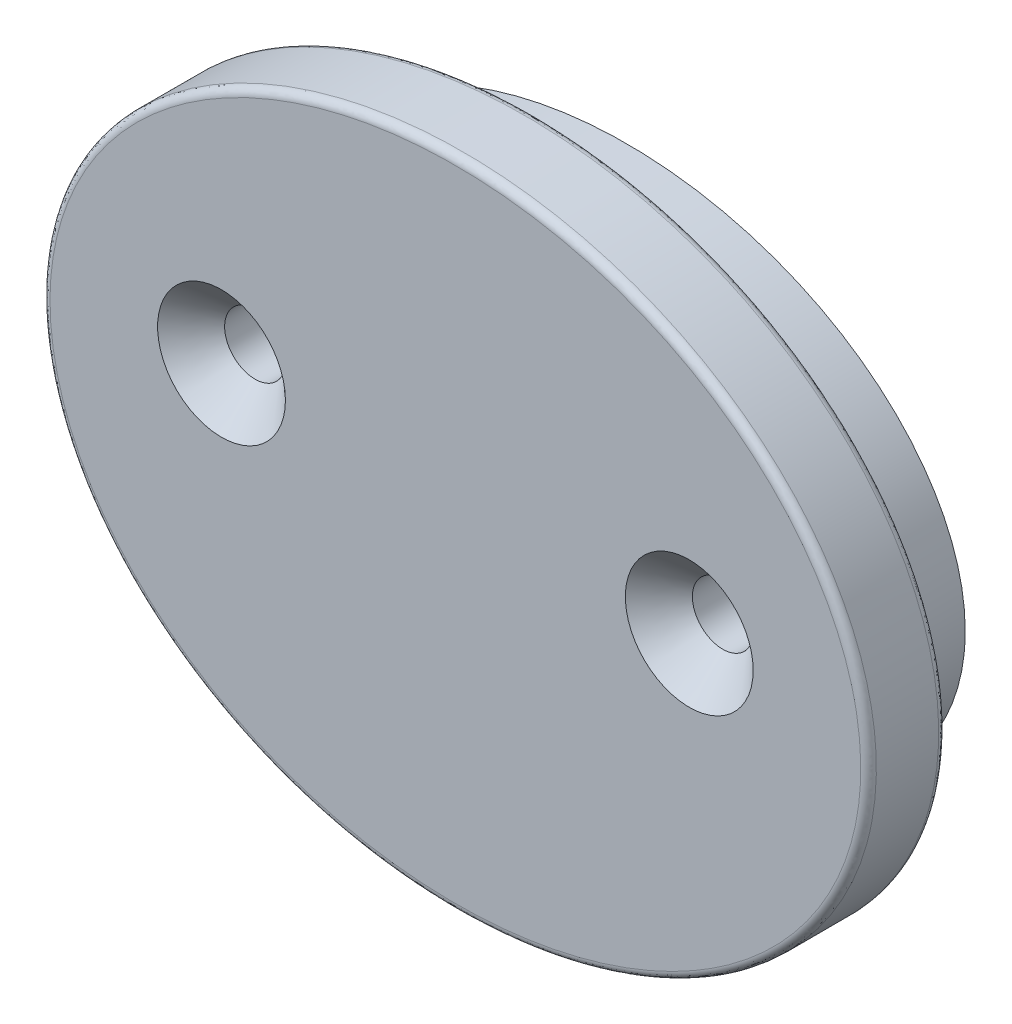
SolidWorks part; units mm, degrees
ref_plane "Ebene vorne" through (0, 0, 0) normal (0, 0, 1) x (1, 0, 0)
ref_plane "Ebene oben" through (0, 0, 0) normal (0, 1, 0) x (1, 0, 0)
ref_plane "Ebene rechts" through (0, 0, 0) normal (1, 0, 0) x (0, 0, -1)
sketch "Skizze1" plane through (0, 0, 0) normal (0, 0, 1) x (1, 0, 0)
  ellipse E0 centre (0, 0) end of major axis (21.7, 0) minor radius 16.2
extrude "Aufsatz-Linear austragen1" add sketch "Skizze1" along normal blind 6
sketch "Skizze2" plane through (0, 0, 6) normal (0, 0, 1) x (1, 0, 0)
  ellipse E0 centre (0, 0) end of major axis (26.5, 0) minor radius 21
extrude "Aufsatz-Linear austragen2" add sketch "Skizze2" along normal blind 5
sketch "Skizze3" plane through (0, 0, 11) normal (0, 0, 1) x (1, 0, 0)
  point P0 (-15, 2)
  point P1 (15, 2)
  dimension "D1" = 2
  dimension "D2" = 2
  dimension "D3" = 15
  dimension "D4" = 15
hole_wizard "Formsenkung für M3.5 Linsensenkschraube1" positions "3D-Skizze1" profile "Skizze4" countersink size "M3.5" standard "ANSI Metrisch" end condition through all
sketch3d "3D-Skizze1"
  point P0 (-15, 2, 11)
  point P3 (15, 2, 11)
sketch "Skizze4" plane through (-15, 2, 11) normal (1, 0, 0) x (0, -1, 0)
  line L0 (0, 0) -> (0, 11)
  line L1 (0, 11) -> (1.95, 11)
  line L2 (1.95, 11) -> (1.95, 2.15)
  line L3 (1.95, 2.15) -> (4.1, 0)
  line L5 (4.1, 0) -> (0, 0)
  line L6 (-1.95, 2.15) -> (-4.1, 0) construction
  line L11 (0, -6.35) -> (0, 107.95) construction
  dimension "Bohrerdurchmesser" = 3.9
  dimension "Bohrungstiefe" = 11
  dimension "Senkdurchmesser (Oben)" = 8.2
  dimension "Senkwinkel (Oben)" = 90
sketch "Skizze5" plane through (0, 0, 11) normal (0, 0, 1) x (1, 0, 0)
  point P0 (0, 0)
sketch "Skizze7" plane through (0, 0, 6) normal (0, 0, -1) x (-1, 0, 0)
  ellipse E0 centre (0, 0) end of major axis (-21.8, 0) minor radius 16.3 construction
fillet "Verrundung1" radius 0.5 2 edges at (26.5, 0, 11) (26.5, 0, 6)
